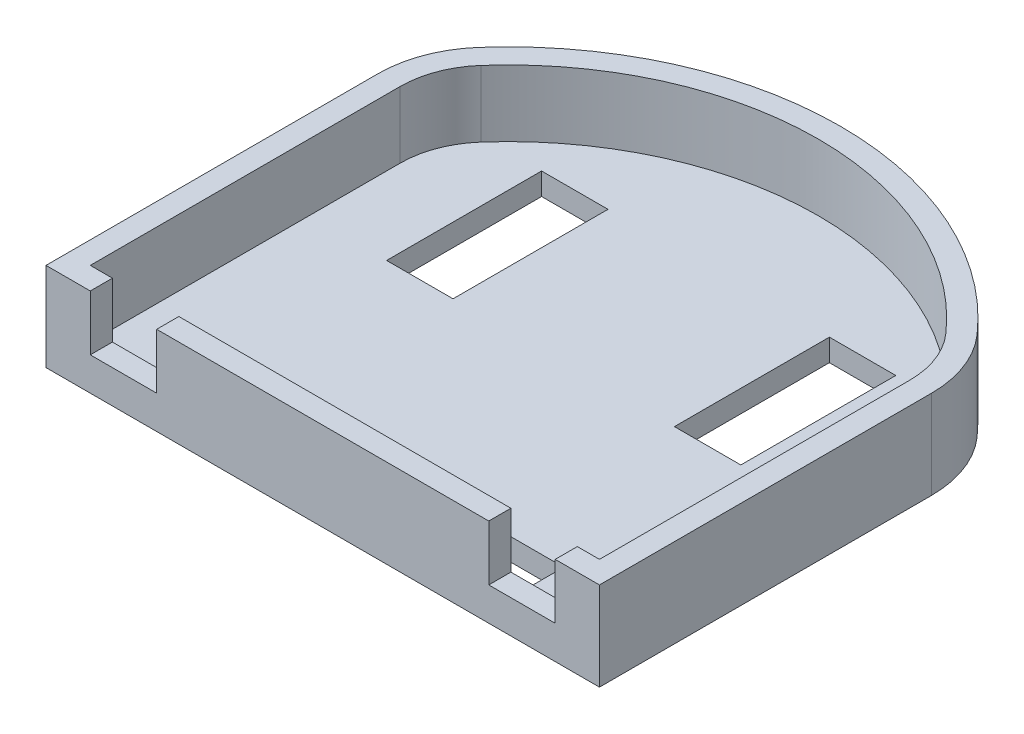
SolidWorks part; units mm, degrees
ref_plane "Front Plane" through (0, 0, 0) normal (0, 0, 1) x (1, 0, 0)
ref_plane "Top Plane" through (0, 0, 0) normal (0, 1, 0) x (1, 0, 0)
ref_plane "Right Plane" through (0, 0, 0) normal (1, 0, 0) x (0, 0, -1)
sketch "Sketch1" plane through (0, 0, 0) normal (0, 1, 0) x (1, 0, 0)
  line L0 (0, 66.1019) -> (0, -75.2194) construction
  line L1 (0, -165) -> (0, 165) construction
  line L2 (125, 66.1438) -> (125, -83.8562)
  line L3 (-125, 66.1438) -> (-125, -83.8562)
  line L4 (125, -83.8562) -> (-125, -83.8562)
  arc A1 (112.5, 99.2157) -> (-112.5, 99.2157) centre (0, 0) ccw
  arc A2 (125, 66.1438) -> (112.5, 99.2157) centre (75, 66.1438) ccw
  arc A3 (-125, 66.1438) -> (-112.5, 99.2157) centre (-75, 66.1438) cw
  point P11 (0, -83.8562)
  point P13 (125, 82.9156)
  point P16 (-125, 82.9156)
  dimension "D1" = 50
  dimension "D3" = 150
  dimension "D2" = 250
  dimension "D4" = 150
extrude "Boss-Extrude1" add sketch "Sketch1" along normal blind 40
shell "Shell1" thickness 10
sketch "Sketch2" plane through (0, 10, 0) normal (0, 1, 0) x (1, 0, 0)
  line L0 (0, 112.9562) -> (0, -37.5156) construction
  line L1 (0, -22) -> (0, 22) construction
  line L2 (-50, 95) -> (-50, 25)
  line L3 (50, 95) -> (80, 95)
  line L4 (50, 95) -> (50, 25)
  line L5 (50, 25) -> (80, 25)
  line L6 (80, 95) -> (80, 25)
  line L7 (50, 95) -> (80, 25) construction
  line L8 (50, 25) -> (80, 95) construction
  line L9 (-50, 95) -> (-80, 25) construction
  line L10 (-50, 25) -> (-80, 95) construction
  line L11 (-50, 95) -> (-80, 95)
  line L12 (-80, 95) -> (-80, 25)
  line L13 (-50, 25) -> (-80, 25)
  line L14 (-22, 0) -> (22, 0) construction
  line L16 (-80, -70) -> (80, -70)
  line L17 (-80, -70) -> (-80, -55)
  line L18 (-80, -55) -> (80, -55)
  line L19 (80, -70) -> (80, -55)
  line L20 (-80, -70) -> (80, -55) construction
  line L21 (-80, -55) -> (80, -70) construction
  point P5 (65, 60)
  point P14 (-65, 60)
  point P17 (0, -62.5)
  dimension "D1" = 100
  dimension "D2" = 25
  dimension "D3" = 70
  dimension "D4" = 30
  dimension "D5" = 55
  dimension "D6" = 15
  dimension "D7" = 160
extrude "Cut-Extrude1" cut sketch "Sketch2" against normal through all
sketch "Sketch3" plane through (0, 0, 83.8562) normal (0, 0, 1) x (1, 0, 0)
  line L0 (-125, 40) -> (125, 40) construction
  line L1 (-105, 65) -> (-75, 65)
  line L2 (-105, 65) -> (-105, 15)
  line L3 (-105, 15) -> (-75, 15)
  line L4 (-75, 65) -> (-75, 15)
  line L5 (-105, 65) -> (-75, 15) construction
  line L6 (-105, 15) -> (-75, 65) construction
  line L7 (-125, 40) -> (-125, 0) construction
  line L8 (0, -35.75) -> (0, 35.75) construction
  line L9 (105, 15) -> (75, 15)
  line L10 (105, 65) -> (75, 65)
  line L11 (75, 65) -> (75, 15)
  line L12 (105, 65) -> (105, 15)
  point P0 (-90, 40)
  dimension "D1" = 50
  dimension "D2" = 30
  dimension "D3" = 20
extrude "Cut-Extrude2" cut sketch "Sketch3" against normal up to next
